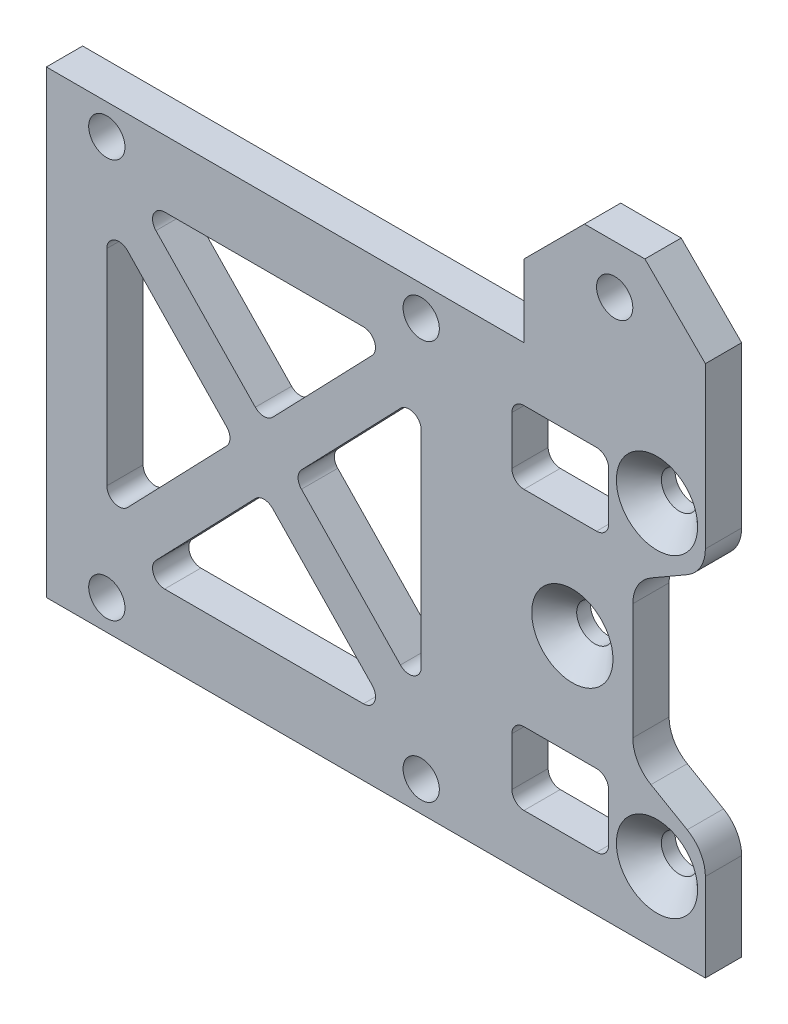
SolidWorks part; units mm, degrees
material "Thornel Mat VMA"
ref_plane "前视基准面" through (0, 0, 0) normal (0, 0, 1) x (1, 0, 0)
ref_plane "上视基准面" through (0, 0, 0) normal (0, 1, 0) x (1, 0, 0)
ref_plane "右视基准面" through (0, 0, 0) normal (1, 0, 0) x (0, 0, -1)
sketch "草图1" plane through (0, 0, 0) normal (0, 0, 1) x (1, 0, 0)
  line L0 (0, 0) -> (-12.4597, 0) construction
  line L1 (13, -16.5) -> (-13, -16.5) construction
  line L2 (13, -16.5) -> (13, 16.5) construction
  line L3 (13, 16.5) -> (-13, 16.5) construction
  line L4 (-13, -16.5) -> (-13, 16.5) construction
  line L5 (13, -16.5) -> (-13, 16.5) construction
  line L6 (13, 16.5) -> (-13, -16.5) construction
  line L7 (0, 0) -> (0, 10.3016) construction
  line L8 (-20.5, -14.5) -> (-28.5, -14.5) construction
  line L9 (36.5, -19) -> (-18, -19)
  line L10 (36.5, -19) -> (36.5, 19) construction
  line L12 (-36.5, -19) -> (-36.5, 19) construction
  line L13 (36.5, -19) -> (-36.5, 19) construction
  line L14 (36.5, 19) -> (-36.5, -19) construction
  line L15 (-20.5, 8.5) -> (-28.5, 8.5) construction
  line L16 (-20.5, 8.5) -> (-20.5, 14.5) construction
  line L17 (-20.5, 14.5) -> (-28.5, 14.5) construction
  line L18 (-28.5, 8.5) -> (-28.5, 14.5) construction
  line L19 (-20.5, 8.5) -> (-28.5, 14.5) construction
  line L20 (-20.5, 14.5) -> (-28.5, 8.5) construction
  line L21 (-28.5, -8.5) -> (-28.5, -14.5) construction
  line L22 (-20.5, -8.5) -> (-28.5, -8.5) construction
  line L23 (-20.5, -8.5) -> (-20.5, -14.5) construction
  line L24 (20.5, -8.5) -> (20.5, -14.5)
  line L25 (20.5, -8.5) -> (28.5, -8.5)
  line L26 (28.5, -8.5) -> (28.5, -14.5)
  line L27 (20.5, -14.5) -> (28.5, -14.5)
  line L28 (20.5, 14.5) -> (28.5, 14.5)
  line L29 (28.5, 8.5) -> (28.5, 14.5)
  line L30 (20.5, 8.5) -> (28.5, 8.5)
  line L31 (20.5, 8.5) -> (20.5, 14.5)
  line L32 (-28.5, -11.5) -> (-24.5, -11.5) construction
  line L33 (24.5, 14.5) -> (24.5, 12.5) construction
  line L34 (36.5, 19) -> (36.5, 10)
  line L42 (-18, 19) -> (-18, -19)
  line L43 (36.5, 19) -> (36.5, 30)
  line L44 (21.5, 19) -> (-18, 19)
  line L48 (-13, -10.9771) -> (-2.4295, 0)
  line L49 (13, -13.5) -> (-13, -13.5) construction
  line L50 (13, -13.5) -> (13, 13.5) construction
  line L51 (13, 13.5) -> (-13, 13.5) construction
  line L52 (-13, -13.5) -> (-13, 13.5) construction
  line L53 (13, -13.5) -> (-13, 13.5) construction
  line L54 (13, 13.5) -> (-13, -13.5) construction
  line L55 (-10.5705, -13.5) -> (0, -2.5229)
  line L56 (-10.5705, 13.5) -> (0, 2.5229)
  line L57 (-13, 10.9771) -> (-2.4295, 0)
  line L58 (0, 2.5229) -> (10.5705, 13.5)
  line L59 (-10.5705, 13.5) -> (10.5705, 13.5)
  line L60 (0, -2.5229) -> (10.5705, -13.5)
  line L61 (2.4295, 0) -> (13, 10.9771)
  line L62 (2.4295, 0) -> (13, -10.9771)
  line L63 (13, 10.9771) -> (13, -10.9771)
  line L64 (-10.5705, -13.5) -> (10.5705, -13.5)
  line L65 (-13, -10.9771) -> (-13, 10.9771)
  line L71 (32.5, 13) -> (32.5, -13) construction
  line L72 (25.5, 0) -> (32.5, 0) construction
  line L75 (36.5, 10) -> (30.5, 6.5359)
  line L76 (30.5, 6.5359) -> (30.5, -6.5359)
  line L77 (30.5, -6.5359) -> (36.5, -10)
  line L79 (36.5, -10) -> (36.5, -19)
  line L80 (36.5, 30) -> (21.5, 30)
  line L81 (21.5, 30) -> (21.5, 19)
  line L83 (29, 26) -> (29, 30) construction
  circle A0 centre (-13, 16.5) radius 1.5
  circle A1 centre (-13, -16.5) radius 1.5
  circle A2 centre (13, -16.5) radius 1.5
  circle A3 centre (13, 16.5) radius 1.5
  circle A4 centre (-32.5, 13) radius 1.5 construction
  circle A5 centre (-32.5, -13) radius 1.5 construction
  circle A6 centre (32.5, -13) radius 1.5
  circle A7 centre (32.5, 13) radius 1.5
  circle A18 centre (25.5, 0) radius 1.5
  circle A19 centre (29, 26) radius 1.5
  point P0 (0, 0)
  point P25 (-24.5, 11.5)
  dimension "D1" = 3
  dimension "D13" = 5
  dimension "D14" = 15
  dimension "D2" = 33
  dimension "D3" = 26
  dimension "D4" = 26
  dimension "D5" = 65
  dimension "D6" = 2.5
  dimension "D7" = 4
  dimension "D8" = 6
  dimension "D9" = 8
  dimension "D10" = 49
  dimension "D11" = 23
  dimension "D12" = 5
  dimension "D15" = 4
  dimension "D16" = 13
  dimension "D20" = 3
  dimension "D22" = 3.5
  dimension "D23" = 7
  dimension "D24" = 9
  dimension "D25" = 5
  dimension "D26" = 60
extrude "凸台-拉伸1" add sketch "草图1" along normal blind 3
hole_wizard "M3 六角凹锥坑螺钉的锥形沉头孔1" positions "3D草图1" profile "草图2" countersink size "M3" standard "ISO" end condition through all
sketch3d "3D草图1"
  line L4 (32.5, 13, 3) -> (32.5, 13, 0) construction
  line L5 (25.5, 0, 3) -> (25.5, 0, 0) construction
  line L6 (32.5, -13, 3) -> (32.5, -13, 0) construction
  point P16 (32.5, 13, 3)
  point P20 (25.5, 0, 3)
  point P24 (32.5, -13, 3)
sketch "草图2" plane through (32.5, 13, 3) normal (1, 0, 0) x (0, -1, 0)
  line L0 (0, 0) -> (0, 3)
  line L1 (0, 3) -> (1.5, 3)
  line L2 (1.5, 3) -> (1.5, 1.86)
  line L3 (1.5, 1.86) -> (3.36, 0)
  line L5 (3.36, 0) -> (0, 0)
  line L6 (-1.5, 1.86) -> (-3.36, 0) construction
  line L11 (0, -6.35) -> (0, 107.95) construction
  dimension "通孔孔直径" = 3
  dimension "通孔孔深度" = 3
  dimension "近端锥形沉头孔直径" = 6.72
  dimension "近端锥形沉头孔角度" = 90
fillet "圆角1" radius 1 20 edges at (28.5, 8.5, 1.5) (20.5, 14.5, 1.5) (20.5, 8.5, 1.5) (20.5, -14.5, 1.5) (28.5, -14.5, 1.5) (28.5, -8.5, 1.5) (20.5, -8.5, 1.5) (28.5, 14.5, 1.5) (2.4295, 0, 1.5) (13, -10.9771, 1.5) (13, 10.9771, 1.5) (0, -2.5229, 1.5) (-10.5705, -13.5, 1.5) (10.5705, -13.5, 1.5) (0, 2.5229, 1.5) (10.5705, 13.5, 1.5) (-2.4295, 0, 1.5) (-13, 10.9771, 1.5) (-13, -10.9771, 1.5) (-10.5705, 13.5, 1.5)
chamfer "倒角1" distance 5 angle 45 2 edges at (21.5, 30, 1.5) (36.5, 30, 1.5)
fillet "圆角2" radius 3 4 edges at (36.5, 10, 1.5) (36.5, -10, 1.5) (30.5, -6.5359, 1.5) (30.5, 6.5359, 1.5)
